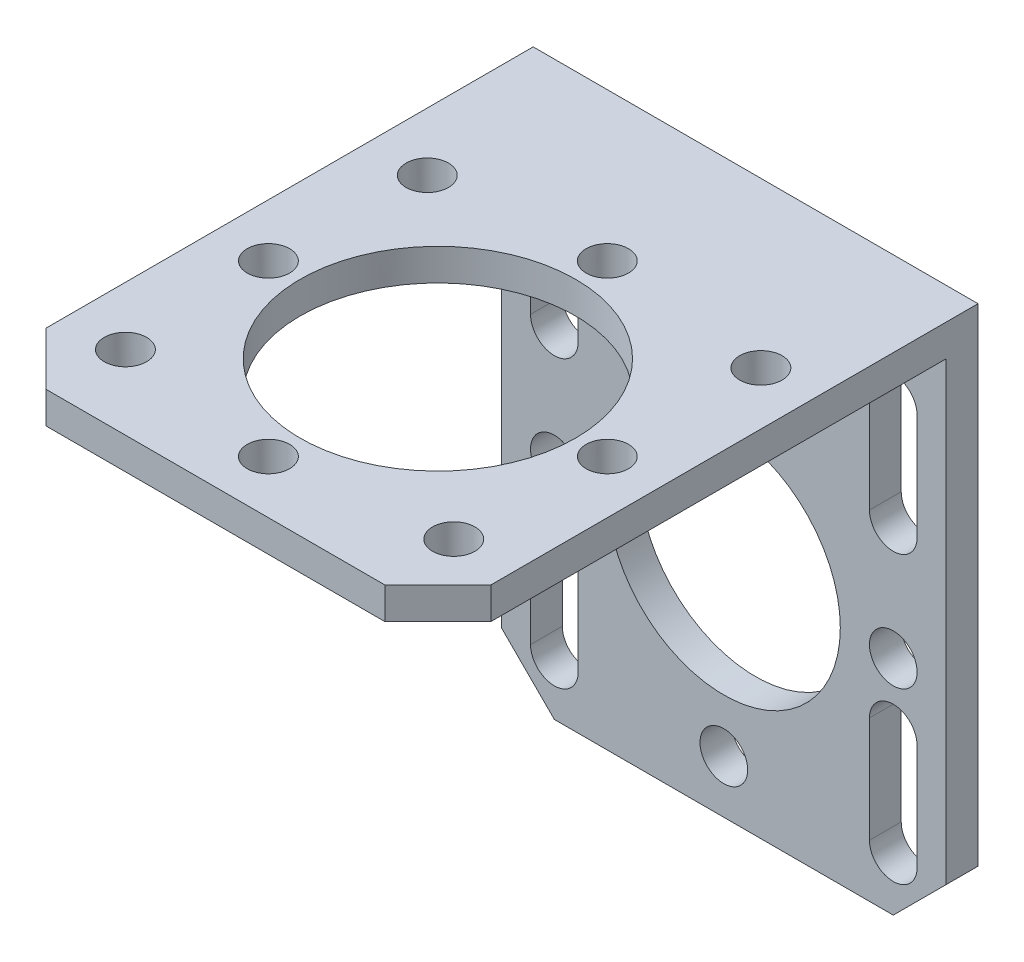
SolidWorks part; units mm, degrees
ref_plane "정면" through (0, 0, 0) normal (0, 0, 1) x (1, 0, 0)
ref_plane "윗면" through (0, 0, 0) normal (0, 1, 0) x (1, 0, 0)
ref_plane "우측면" through (0, 0, 0) normal (1, 0, 0) x (0, 0, -1)
sketch "스케치1" plane through (0, 0, 0) normal (0, 0, 1) x (1, 0, 0)
  line L1 (-21, 25.5) -> (21, 25.5)
  line L2 (-21, 25.5) -> (-21, -25.5)
  line L3 (-21, -25.5) -> (21, -25.5)
  line L4 (21, 25.5) -> (21, -25.5)
  line L5 (-21, 25.5) -> (21, -25.5) construction
  line L6 (-21, -25.5) -> (21, 25.5) construction
  point P0 (0, 0)
  dimension "D1" = 42
  dimension "D2" = 51
extrude "보스-돌출1" add sketch "스케치1" along normal blind 3
sketch "스케치2" plane through (0, 0, 3) normal (0, 0, 1) x (1, 0, 0)
  line L0 (21, -25.5) -> (21, 25.5) construction
  line L1 (-21, 25.5) -> (21, 25.5)
  line L2 (-21, 25.5) -> (-21, 22.5)
  line L3 (-21, 22.5) -> (21, 22.5)
  line L4 (21, 25.5) -> (21, 22.5)
  dimension "D1" = 3
extrude "보스-돌출2" add sketch "스케치2" along normal blind 48
chamfer "모따기1" distance 5 angle 45 4 edges at (21, -25.5, 1.5) (-21, -25.5, 1.5) (21, 24, 51) (-21, 24, 51)
sketch "스케치3" plane through (0, 22.5, 0) normal (0, -1, 0) x (1, 0, 0)
  line L0 (-16, 51) -> (16, 51) construction
  line L1 (21, 46) -> (21, 3) construction
  line L2 (-15.5, 44) -> (23.51, 44) construction
  line L3 (-21, 46) -> (-21, 3) construction
  circle A0 centre (0, 30) radius 16 construction
  circle A1 centre (0, 30) radius 13
  circle A3 centre (-15.5, 44) radius 2
  circle A4 centre (-15.5, 15.5) radius 2
  circle A5 centre (0, 46) radius 2
  circle A6 centre (15.5, 44) radius 2
  circle A7 centre (16, 30) radius 2
  circle A8 centre (0, 14) radius 2
  circle A9 centre (-16, 30) radius 2
  circle A10 centre (16, 15.5) radius 2
  point P25 (0, 30)
  point P27 (0, 0)
  point P28 (0, 0)
  point P29 (15.709, 12.3527)
  dimension "D1" = 32
  dimension "D3" = 26
  dimension "D4" = 21
  dimension "D5" = 4
  dimension "D6" = 28.5
  dimension "D7" = 4
  dimension "D9" = 5
  dimension "D11" = 4
  dimension "D12" = 4
  dimension "D13" = 4
  dimension "D2" = 21
  dimension "D8" = 31
  dimension "D14" = 7
  dimension "D15" = 5.5
  dimension "D16" = 5.5
  dimension "D17" = 5
  dimension "D10" = 4
extrude "컷-돌출1" cut sketch "스케치3" against normal blind 48
sketch "스케치4" plane through (0, 0, 3) normal (0, 0, 1) x (1, 0, 0)
  line L0 (-16, -25.5) -> (16, -25.5) construction
  line L1 (-16, 16.5) -> (-16, 6.5) construction
  line L2 (-13.75, 16.5) -> (-13.75, 6.5)
  line L3 (21, -20.5) -> (21, 22.5) construction
  line L4 (-16, -10.5) -> (-16, -20.5) construction
  line L5 (-13.75, -10.5) -> (-13.75, -20.5)
  line L6 (-18.25, -10.5) -> (-18.25, -20.5)
  line L7 (16, -10.5) -> (16, -20.5) construction
  line L8 (13.75, -10.5) -> (13.75, -20.5)
  line L9 (18.25, -10.5) -> (18.25, -20.5)
  line L10 (-18.25, 16.5) -> (-18.25, 6.5)
  line L14 (0, -28.05) -> (0, 28.05) construction
  line L15 (16, 16.5) -> (16, 6.5) construction
  line L16 (13.75, 16.5) -> (13.75, 6.5)
  line L17 (18.25, 16.5) -> (18.25, 6.5)
  circle A0 centre (0, -20.5) radius 2.25
  circle A1 centre (0, -4.5) radius 11
  circle A2 centre (-16, -4.5) radius 2.25
  circle A3 centre (0, 11.5) radius 2.25
  circle A4 centre (16, -4.5) radius 2.25
  arc A5 (-13.75, -10.5) -> (-18.25, -10.5) centre (-16, -10.5) ccw
  arc A6 (-18.25, -20.5) -> (-13.75, -20.5) centre (-16, -20.5) ccw
  arc A7 (13.75, -10.5) -> (18.25, -10.5) centre (16, -10.5) cw
  arc A8 (18.25, -20.5) -> (13.75, -20.5) centre (16, -20.5) cw
  arc A11 (-13.75, 16.5) -> (-18.25, 16.5) centre (-16, 16.5) ccw
  arc A12 (-18.25, 6.5) -> (-13.75, 6.5) centre (-16, 6.5) ccw
  arc A13 (13.75, 16.5) -> (18.25, 16.5) centre (16, 16.5) cw
  arc A14 (18.25, 6.5) -> (13.75, 6.5) centre (16, 6.5) cw
  point P10 (-16, -15.5)
  point P17 (0, -4.5)
  point P24 (-16, 11.5)
  point P29 (16, -15.5)
  point P38 (-21, 13.7985)
  point P41 (16, 11.5)
  dimension "D3" = 4.5
  dimension "D4" = 22
  dimension "D6" = 21
  dimension "D8" = 2.25
  dimension "D9" = 10
  dimension "D11" = 4.5
  dimension "D12" = 32
  dimension "D1" = 5
  dimension "D2" = 21
  dimension "D5" = 21
  dimension "D10" = 0
  dimension "D14" = 10
  dimension "D7" = 4
extrude "컷-돌출2" cut sketch "스케치4" against normal blind 48
